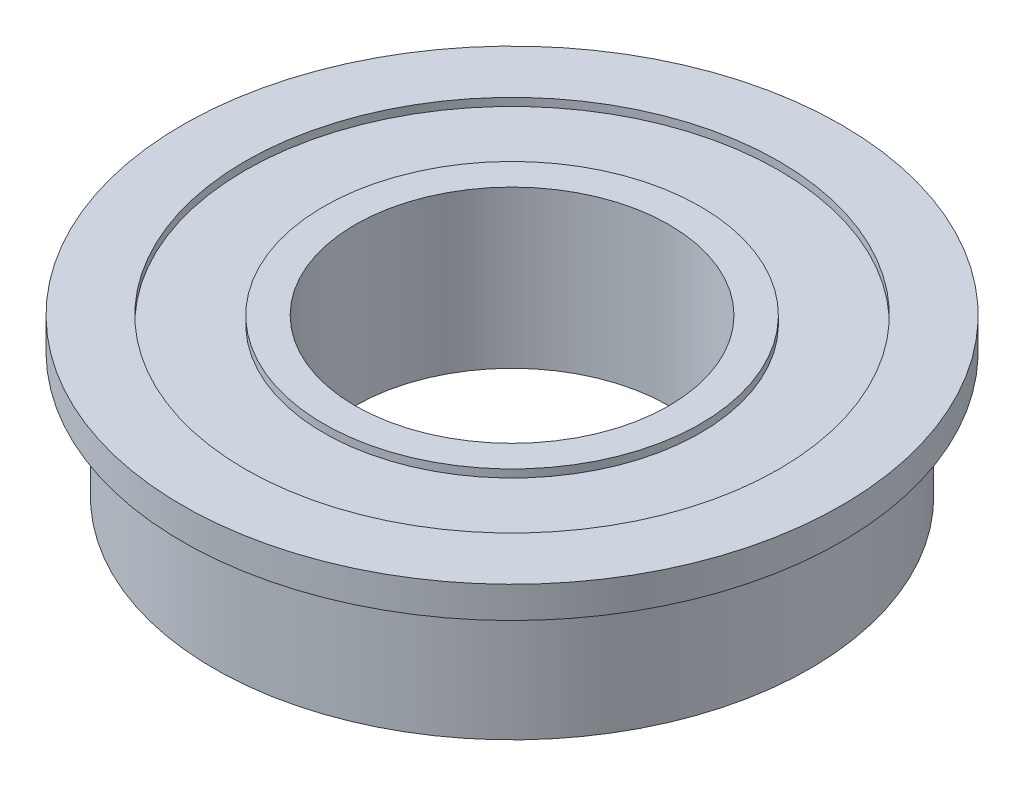
SolidWorks part; units mm, degrees
material "AISI 304"
ref_plane "前视基准面" through (0, 0, 0) normal (0, 0, 1) x (1, 0, 0)
ref_plane "上视基准面" through (0, 0, 0) normal (0, 1, 0) x (1, 0, 0)
ref_plane "右视基准面" through (0, 0, 0) normal (1, 0, 0) x (0, 0, -1)
other "Configuration Table"
sketch "草图2" plane through (0, 0, 0) normal (0, 0, 1) x (1, 0, 0)
  line L0 (0, 0) -> (0, 0.8612) construction
  line L1 (0, 0) -> (1.8966, 0) construction
  line L2 (5, 2.5) -> (5, -2.5)
  line L3 (5, 2.5) -> (6, 2.5)
  line L4 (6, 2.5) -> (6, 2.25)
  line L5 (6, 2.25) -> (8.5, 2.25)
  line L6 (8.5, 2.25) -> (8.5, 2.5)
  line L7 (8.5, 2.5) -> (9.5, 2.5)
  line L8 (9.5, 1.5) -> (9.5, -2.5)
  line L9 (8.5, -2.5) -> (9.5, -2.5)
  line L10 (8.5, -2.25) -> (8.5, -2.5)
  line L11 (6, -2.25) -> (8.5, -2.25)
  line L12 (6, -2.5) -> (6, -2.25)
  line L13 (5, -2.5) -> (6, -2.5)
  line L14 (9.5, 2.5) -> (10.5, 2.5)
  line L15 (10.5, 2.5) -> (10.5, 1.5)
  line L16 (10.5, 1.5) -> (9.5, 1.5)
  point P20 (5, 0)
  dimension "内径" = 10
  dimension "外径" = 19
  dimension "厚度" = 5
  dimension "D1" = 1
  dimension "D2" = 0.25
  dimension "D3" = 21
  dimension "D4" = 1
revolve "旋转1" add sketch "草图2" angle 360 about L0
equation "\"D1@草图2\"=(\"外径@草图2\"-\"内径@草图2\")/9"
equation "\"D2@草图2\"=\"厚度@草图2\"/20"
equation "\"内径\" = 10"
equation "\"外径\" = 19"
equation "\"法兰外径\" = 21"
equation "\"法兰厚度\" = 1"
equation "\"总厚度\"= 5"
equation "\"外径@草图2\"=\"外径\""
equation "\"厚度@草图2\"=\"总厚度\""
equation "\"内径@草图2\"=\"内径\""
equation "\"D3@草图2\"=\"法兰外径\""
equation "\"D4@草图2\"=\"法兰厚度\""
